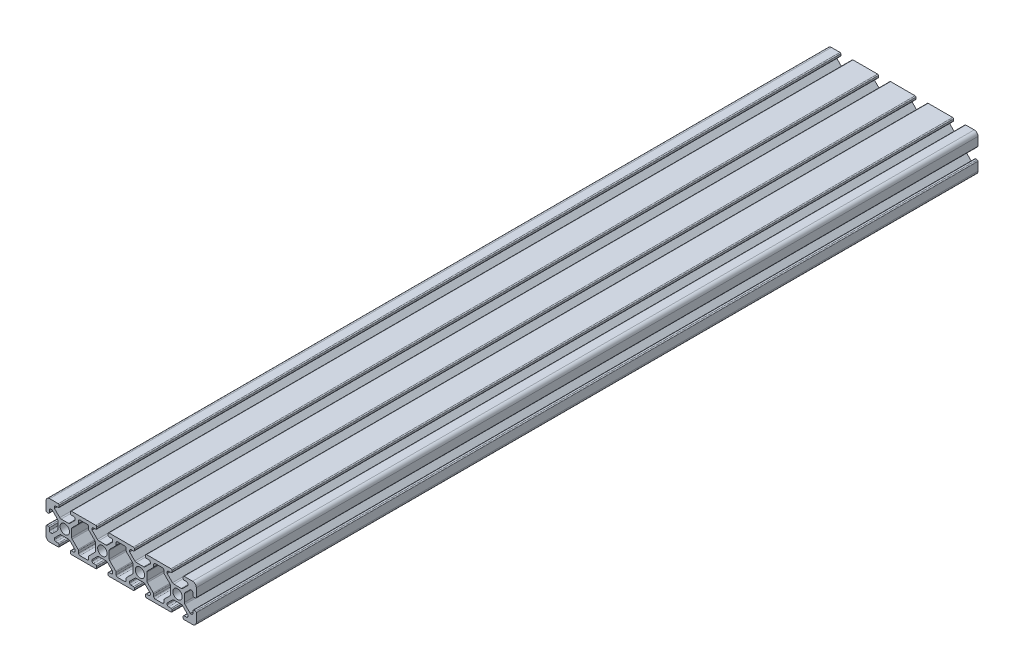
SolidWorks part; units mm, degrees
material "6063-T5"
ref_plane "Front Plane" through (0, 0, 0) normal (0, 0, 1) x (1, 0, 0)
ref_plane "Top Plane" through (0, 0, 0) normal (0, 1, 0) x (1, 0, 0)
ref_plane "Right Plane" through (0, 0, 0) normal (1, 0, 0) x (0, 0, -1)
sketch "Sketch1" plane through (0, 0, 0) normal (0, 0, 1) x (1, 0, 0)
  line L0 (-41.935, 2.3415) -> (-37.435, 2.3415)
  line L1 (36.065, 4.3415) -> (36.065, 8.8415)
  line L2 (34.065, 22.3415) -> (29.565, 22.3415)
  line L3 (-43.935, 20.3415) -> (-43.935, 15.8415)
  line L4 (-10.935, 21.8415) -> (-10.935, 21.0415)
  line L5 (-16.935, 21.8415) -> (-16.935, 21.0415)
  line L6 (-36.935, 21.8415) -> (-36.935, 21.0415)
  line L7 (-30.935, 21.8415) -> (-30.935, 21.0415)
  line L8 (-37.435, 22.3415) -> (-41.935, 22.3415)
  line L9 (9.065, 21.8415) -> (9.065, 21.0415)
  line L10 (3.065, 21.8415) -> (3.065, 21.0415)
  line L11 (29.065, 21.8415) -> (29.065, 21.0415)
  line L12 (23.065, 21.8415) -> (23.065, 21.0415)
  line L13 (-10.935, 3.6415) -> (-10.935, 2.8415)
  line L14 (-16.935, 3.6415) -> (-16.935, 2.8415)
  line L15 (9.065, 3.6415) -> (9.065, 2.8415)
  line L16 (3.065, 3.6415) -> (3.065, 2.8415)
  line L17 (29.065, 3.6415) -> (29.065, 2.8415)
  line L18 (23.065, 3.6415) -> (23.065, 2.8415)
  line L19 (-30.935, 3.6415) -> (-30.935, 2.8415)
  line L20 (-36.935, 3.6415) -> (-36.935, 2.8415)
  line L21 (-30.435, 22.3415) -> (-17.435, 22.3415) construction
  line L22 (-17.435, 22.3415) -> (-30.435, 22.3415)
  line L23 (2.565, 22.3415) -> (-10.435, 22.3415)
  line L24 (22.565, 22.3415) -> (9.565, 22.3415)
  line L25 (29.565, 2.3415) -> (34.065, 2.3415)
  line L26 (9.565, 2.3415) -> (22.565, 2.3415)
  line L27 (-10.435, 2.3415) -> (2.565, 2.3415)
  line L28 (-30.435, 2.3415) -> (-17.435, 2.3415)
  line L29 (35.565, 15.3415) -> (34.765, 15.3415)
  line L30 (35.565, 9.3415) -> (34.765, 9.3415)
  line L31 (-43.435, 15.3415) -> (-42.635, 15.3415)
  line L32 (-43.435, 9.3415) -> (-42.635, 9.3415)
  line L33 (-43.935, 8.8415) -> (-43.935, 4.3415)
  line L34 (36.065, 15.8415) -> (36.065, 20.3415)
  line L35 (-42.135, 15.8415) -> (-42.135, 17.0915)
  line L36 (-38.685, 20.5415) -> (-37.435, 20.5415)
  line L37 (34.265, 17.0915) -> (34.265, 15.8415)
  line L38 (30.815, 4.1415) -> (29.565, 4.1415)
  line L39 (-42.135, 7.5915) -> (-42.135, 8.8415)
  line L40 (-30.435, 20.5415) -> (-29.185, 20.5415)
  line L41 (-37.435, 4.1415) -> (-38.685, 4.1415)
  line L42 (-10.435, 20.5415) -> (-9.185, 20.5415)
  line L43 (-17.435, 4.1415) -> (-18.685, 4.1415)
  line L44 (9.565, 20.5415) -> (10.815, 20.5415)
  line L45 (2.565, 4.1415) -> (1.315, 4.1415)
  line L46 (29.565, 20.5415) -> (30.815, 20.5415)
  line L47 (22.565, 4.1415) -> (21.315, 4.1415)
  line L48 (34.265, 8.8415) -> (34.265, 7.5915)
  line L49 (-31.2649, 16.2843) -> (-28.435, 19.1142)
  line L50 (-31.2649, 8.3986) -> (-28.435, 5.5687)
  line L51 (-11.2649, 16.2843) -> (-8.435, 19.1142)
  line L52 (-9.9921, 15.0116) -> (-6.8546, 18.149)
  line L53 (-16.6051, 16.2843) -> (-19.435, 19.1142)
  line L54 (-21.0153, 18.149) -> (-17.8778, 15.0116)
  line L55 (-16.6051, 8.3986) -> (-19.435, 5.5687)
  line L56 (-21.0153, 6.5339) -> (-17.8778, 9.6714)
  line L57 (3.3949, 16.2843) -> (0.565, 19.1142)
  line L58 (-1.0153, 18.149) -> (2.1222, 15.0116)
  line L59 (3.3949, 8.3986) -> (0.565, 5.5687)
  line L60 (-1.0153, 6.5339) -> (2.1222, 9.6714)
  line L61 (23.3949, 16.2843) -> (20.565, 19.1142)
  line L62 (18.9847, 18.149) -> (22.1222, 15.0116)
  line L63 (23.3949, 8.3986) -> (20.565, 5.5687)
  line L64 (18.9847, 6.5339) -> (22.1222, 9.6714)
  line L65 (-9.9921, 9.6714) -> (-6.8546, 6.5339)
  line L66 (-29.9921, 15.0116) -> (-26.8546, 18.149)
  line L67 (-37.8778, 9.6714) -> (-40.7077, 6.8415)
  line L68 (-36.6051, 8.3986) -> (-39.435, 5.5687)
  line L69 (-36.6051, 16.2843) -> (-39.435, 19.1142)
  line L70 (-11.2649, 8.3986) -> (-8.435, 5.5687)
  line L71 (-29.9921, 9.6714) -> (-26.8546, 6.5339)
  line L72 (8.7351, 16.2843) -> (11.565, 19.1142)
  line L73 (-37.8778, 15.0116) -> (-40.7077, 17.8415)
  line L74 (10.0079, 15.0116) -> (13.1454, 18.149)
  line L75 (10.0079, 9.6714) -> (13.1454, 6.5339)
  line L76 (8.7351, 8.3986) -> (11.565, 5.5687)
  line L77 (28.7351, 16.2843) -> (31.565, 19.1142)
  line L78 (30.0079, 15.0116) -> (32.8378, 17.8415)
  line L79 (30.0079, 9.6714) -> (32.8378, 6.8415)
  line L80 (28.7351, 8.3986) -> (31.565, 5.5687)
  line L81 (-15.898, 15.9915) -> (-11.972, 15.9915)
  line L82 (-25.885, 20.5415) -> (-21.985, 20.5415)
  line L83 (-29.185, 4.1415) -> (-30.435, 4.1415)
  line L84 (-28.435, 19.7915) -> (-28.435, 19.1142)
  line L85 (-9.185, 4.1415) -> (-10.435, 4.1415)
  line L86 (-39.435, 19.7915) -> (-39.435, 19.1142)
  line L87 (10.815, 4.1415) -> (9.565, 4.1415)
  line L88 (-19.435, 19.7915) -> (-19.435, 19.1142)
  line L89 (-18.685, 20.5415) -> (-17.435, 20.5415)
  line L90 (1.315, 20.5415) -> (2.565, 20.5415)
  line L91 (-10.285, 14.3044) -> (-10.285, 10.3785)
  line L92 (-11.972, 8.6915) -> (-15.898, 8.6915)
  line L93 (-17.585, 10.3785) -> (-17.585, 14.3044)
  line L94 (21.315, 20.5415) -> (22.565, 20.5415)
  line L95 (0.565, 19.7915) -> (0.565, 19.1142)
  line L96 (-8.435, 19.7915) -> (-8.435, 19.1142)
  line L97 (-30.285, 14.3044) -> (-30.285, 10.3785)
  line L98 (-31.972, 8.6915) -> (-35.898, 8.6915)
  line L99 (-37.585, 10.3785) -> (-37.585, 14.3044)
  line L100 (-35.898, 15.9915) -> (-31.972, 15.9915)
  line L101 (4.102, 15.9915) -> (8.028, 15.9915)
  line L102 (9.715, 14.3044) -> (9.715, 10.3785)
  line L103 (8.028, 8.6915) -> (4.102, 8.6915)
  line L104 (2.415, 10.3785) -> (2.415, 14.3044)
  line L105 (24.102, 15.9915) -> (28.028, 15.9915)
  line L106 (29.715, 14.3044) -> (29.715, 10.3785)
  line L107 (28.028, 8.6915) -> (24.102, 8.6915)
  line L108 (22.415, 10.3785) -> (22.415, 14.3044)
  line L109 (20.565, 19.7915) -> (20.565, 19.1142)
  line L110 (11.565, 19.7915) -> (11.565, 19.1142)
  line L111 (-39.435, 4.8915) -> (-39.435, 5.5687)
  line L112 (31.565, 19.7915) -> (31.565, 19.1142)
  line L113 (-19.435, 4.8915) -> (-19.435, 5.5687)
  line L114 (-28.435, 4.8915) -> (-28.435, 5.5687)
  line L115 (0.565, 4.8915) -> (0.565, 5.5687)
  line L116 (-8.435, 4.8915) -> (-8.435, 5.5687)
  line L117 (20.565, 4.8915) -> (20.565, 5.5687)
  line L118 (11.565, 4.8915) -> (11.565, 5.5687)
  line L119 (-41.385, 17.8415) -> (-40.7077, 17.8415)
  line L120 (31.565, 4.8915) -> (31.565, 5.5687)
  line L121 (-41.385, 6.8415) -> (-40.7077, 6.8415)
  line L122 (33.515, 17.8415) -> (32.8378, 17.8415)
  line L123 (-26.635, 19.7915) -> (-26.635, 18.6793)
  line L124 (33.515, 6.8415) -> (32.8378, 6.8415)
  line L125 (-21.235, 19.7915) -> (-21.235, 18.6793)
  line L126 (-5.885, 20.5415) -> (-1.985, 20.5415)
  line L127 (-6.635, 19.7915) -> (-6.635, 18.6793)
  line L128 (-1.235, 19.7915) -> (-1.235, 18.6793)
  line L129 (14.115, 20.5415) -> (18.015, 20.5415)
  line L130 (13.365, 19.7915) -> (13.365, 18.6793)
  line L131 (18.765, 19.7915) -> (18.765, 18.6793)
  line L132 (-26.635, 6.0036) -> (-26.635, 4.8915)
  line L133 (-25.885, 4.1415) -> (-21.985, 4.1415)
  line L134 (-21.235, 4.8915) -> (-21.235, 6.0036)
  line L135 (-6.635, 6.0036) -> (-6.635, 4.8915)
  line L136 (-5.885, 4.1415) -> (-1.985, 4.1415)
  line L137 (-1.235, 4.8915) -> (-1.235, 6.0036)
  line L138 (13.365, 6.0036) -> (13.365, 4.8915)
  line L139 (14.115, 4.1415) -> (18.015, 4.1415)
  line L140 (18.765, 4.8915) -> (18.765, 6.0036)
  circle A0 centre (-33.935, 12.3415) radius 2.5
  circle A1 centre (-13.935, 12.3415) radius 2.5
  circle A2 centre (6.065, 12.3415) radius 2.5
  circle A3 centre (26.065, 12.3415) radius 2.5
  arc A4 (34.065, 2.3415) -> (36.065, 4.3415) centre (34.065, 4.3415) ccw
  arc A5 (36.065, 20.3415) -> (34.065, 22.3415) centre (34.065, 20.3415) ccw
  arc A6 (-41.935, 2.3415) -> (-43.935, 4.3415) centre (-41.935, 4.3415) cw
  arc A7 (-41.935, 22.3415) -> (-43.935, 20.3415) centre (-41.935, 20.3415) ccw
  arc A8 (-31.2649, 16.2843) -> (-31.972, 15.9915) centre (-31.972, 16.9915) cw
  arc A9 (-36.6051, 16.2843) -> (-35.898, 15.9915) centre (-35.898, 16.9915) ccw
  arc A10 (-37.8778, 15.0116) -> (-37.585, 14.3044) centre (-38.585, 14.3044) cw
  arc A11 (-37.8778, 9.6714) -> (-37.585, 10.3785) centre (-38.585, 10.3785) ccw
  arc A12 (-36.6051, 8.3986) -> (-35.898, 8.6915) centre (-35.898, 7.6915) cw
  arc A13 (-31.2649, 8.3986) -> (-31.972, 8.6915) centre (-31.972, 7.6915) ccw
  arc A14 (-11.2649, 8.3986) -> (-11.972, 8.6915) centre (-11.972, 7.6915) ccw
  arc A15 (-16.6051, 8.3986) -> (-15.898, 8.6915) centre (-15.898, 7.6915) cw
  arc A16 (-16.6051, 16.2843) -> (-15.898, 15.9915) centre (-15.898, 16.9915) ccw
  arc A17 (-11.2649, 16.2843) -> (-11.972, 15.9915) centre (-11.972, 16.9915) cw
  arc A18 (3.3949, 8.3986) -> (4.102, 8.6915) centre (4.102, 7.6915) cw
  arc A19 (8.7351, 8.3986) -> (8.028, 8.6915) centre (8.028, 7.6915) ccw
  arc A20 (8.7351, 16.2843) -> (8.028, 15.9915) centre (8.028, 16.9915) cw
  arc A21 (3.3949, 16.2843) -> (4.102, 15.9915) centre (4.102, 16.9915) ccw
  arc A22 (28.7351, 16.2843) -> (28.028, 15.9915) centre (28.028, 16.9915) cw
  arc A23 (23.3949, 16.2843) -> (24.102, 15.9915) centre (24.102, 16.9915) ccw
  arc A24 (23.3949, 8.3986) -> (24.102, 8.6915) centre (24.102, 7.6915) cw
  arc A25 (28.7351, 8.3986) -> (28.028, 8.6915) centre (28.028, 7.6915) ccw
  arc A26 (30.0079, 9.6714) -> (29.715, 10.3785) centre (30.715, 10.3785) cw
  arc A27 (30.0079, 15.0116) -> (29.715, 14.3044) centre (30.715, 14.3044) ccw
  arc A28 (22.1222, 9.6714) -> (22.415, 10.3785) centre (21.415, 10.3785) ccw
  arc A29 (22.1222, 15.0116) -> (22.415, 14.3044) centre (21.415, 14.3044) cw
  arc A30 (10.0079, 9.6714) -> (9.715, 10.3785) centre (10.715, 10.3785) cw
  arc A31 (10.0079, 15.0116) -> (9.715, 14.3044) centre (10.715, 14.3044) ccw
  arc A32 (34.265, 17.0915) -> (33.515, 17.8415) centre (33.515, 17.0915) ccw
  arc A33 (31.565, 19.7915) -> (30.815, 20.5415) centre (30.815, 19.7915) ccw
  arc A34 (34.265, 7.5915) -> (33.515, 6.8415) centre (33.515, 7.5915) cw
  arc A35 (31.565, 4.8915) -> (30.815, 4.1415) centre (30.815, 4.8915) cw
  arc A36 (2.1222, 9.6714) -> (2.415, 10.3785) centre (1.415, 10.3785) ccw
  arc A37 (2.1222, 15.0116) -> (2.415, 14.3044) centre (1.415, 14.3044) cw
  arc A38 (-9.9921, 9.6714) -> (-10.285, 10.3785) centre (-9.285, 10.3785) cw
  arc A39 (-9.9921, 15.0116) -> (-10.285, 14.3044) centre (-9.285, 14.3044) ccw
  arc A40 (-29.9921, 15.0116) -> (-30.285, 14.3044) centre (-29.285, 14.3044) ccw
  arc A41 (-29.9921, 9.6714) -> (-30.285, 10.3785) centre (-29.285, 10.3785) cw
  arc A42 (-17.8778, 9.6714) -> (-17.585, 10.3785) centre (-18.585, 10.3785) ccw
  arc A43 (-17.8778, 15.0116) -> (-17.585, 14.3044) centre (-18.585, 14.3044) cw
  arc A44 (21.315, 4.1415) -> (20.565, 4.8915) centre (21.315, 4.8915) cw
  arc A45 (18.015, 4.1415) -> (18.765, 4.8915) centre (18.015, 4.8915) ccw
  arc A46 (13.365, 4.8915) -> (14.115, 4.1415) centre (14.115, 4.8915) ccw
  arc A47 (10.815, 4.1415) -> (11.565, 4.8915) centre (10.815, 4.8915) ccw
  arc A48 (1.315, 4.1415) -> (0.565, 4.8915) centre (1.315, 4.8915) cw
  arc A49 (20.565, 19.7915) -> (21.315, 20.5415) centre (21.315, 19.7915) cw
  arc A50 (18.015, 20.5415) -> (18.765, 19.7915) centre (18.015, 19.7915) cw
  arc A51 (14.115, 20.5415) -> (13.365, 19.7915) centre (14.115, 19.7915) ccw
  arc A52 (9.065, 21.0415) -> (9.565, 20.5415) centre (9.565, 21.0415) ccw
  arc A53 (9.065, 21.8415) -> (9.565, 22.3415) centre (9.565, 21.8415) cw
  arc A54 (23.065, 21.0415) -> (22.565, 20.5415) centre (22.565, 21.0415) cw
  arc A55 (23.065, 21.8415) -> (22.565, 22.3415) centre (22.565, 21.8415) ccw
  arc A56 (29.065, 21.0415) -> (29.565, 20.5415) centre (29.565, 21.0415) ccw
  arc A57 (29.065, 21.8415) -> (29.565, 22.3415) centre (29.565, 21.8415) cw
  arc A58 (34.765, 15.3415) -> (34.265, 15.8415) centre (34.765, 15.8415) cw
  arc A59 (35.565, 15.3415) -> (36.065, 15.8415) centre (35.565, 15.8415) ccw
  arc A60 (34.765, 9.3415) -> (34.265, 8.8415) centre (34.765, 8.8415) ccw
  arc A61 (35.565, 9.3415) -> (36.065, 8.8415) centre (35.565, 8.8415) cw
  arc A62 (29.065, 2.8415) -> (29.565, 2.3415) centre (29.565, 2.8415) ccw
  arc A63 (29.065, 3.6415) -> (29.565, 4.1415) centre (29.565, 3.6415) cw
  arc A64 (23.065, 2.8415) -> (22.565, 2.3415) centre (22.565, 2.8415) cw
  arc A65 (23.065, 3.6415) -> (22.565, 4.1415) centre (22.565, 3.6415) ccw
  arc A66 (9.065, 2.8415) -> (9.565, 2.3415) centre (9.565, 2.8415) ccw
  arc A67 (9.065, 3.6415) -> (9.565, 4.1415) centre (9.565, 3.6415) cw
  arc A68 (3.065, 2.8415) -> (2.565, 2.3415) centre (2.565, 2.8415) cw
  arc A69 (3.065, 3.6415) -> (2.565, 4.1415) centre (2.565, 3.6415) ccw
  arc A70 (-10.935, 2.8415) -> (-10.435, 2.3415) centre (-10.435, 2.8415) ccw
  arc A71 (-10.935, 3.6415) -> (-10.435, 4.1415) centre (-10.435, 3.6415) cw
  arc A72 (-16.935, 2.8415) -> (-17.435, 2.3415) centre (-17.435, 2.8415) cw
  arc A73 (-16.935, 3.6415) -> (-17.435, 4.1415) centre (-17.435, 3.6415) ccw
  arc A74 (3.065, 21.0415) -> (2.565, 20.5415) centre (2.565, 21.0415) cw
  arc A75 (3.065, 21.8415) -> (2.565, 22.3415) centre (2.565, 21.8415) ccw
  arc A76 (-10.935, 21.0415) -> (-10.435, 20.5415) centre (-10.435, 21.0415) ccw
  arc A77 (-10.935, 21.8415) -> (-10.435, 22.3415) centre (-10.435, 21.8415) cw
  arc A78 (-16.935, 21.0415) -> (-17.435, 20.5415) centre (-17.435, 21.0415) cw
  arc A79 (-16.935, 21.8415) -> (-17.435, 22.3415) centre (-17.435, 21.8415) ccw
  arc A80 (-30.935, 21.0415) -> (-30.435, 20.5415) centre (-30.435, 21.0415) ccw
  arc A81 (-30.435, 22.3415) -> (-30.935, 21.8415) centre (-30.435, 21.8415) ccw
  arc A82 (-30.935, 2.8415) -> (-30.435, 2.3415) centre (-30.435, 2.8415) ccw
  arc A83 (-30.935, 3.6415) -> (-30.435, 4.1415) centre (-30.435, 3.6415) cw
  arc A84 (-36.935, 2.8415) -> (-37.435, 2.3415) centre (-37.435, 2.8415) cw
  arc A85 (-36.935, 3.6415) -> (-37.435, 4.1415) centre (-37.435, 3.6415) ccw
  arc A86 (-43.935, 8.8415) -> (-43.435, 9.3415) centre (-43.435, 8.8415) cw
  arc A87 (-42.635, 9.3415) -> (-42.135, 8.8415) centre (-42.635, 8.8415) cw
  arc A88 (-43.935, 15.8415) -> (-43.435, 15.3415) centre (-43.435, 15.8415) ccw
  arc A89 (-42.635, 15.3415) -> (-42.135, 15.8415) centre (-42.635, 15.8415) ccw
  arc A90 (-37.435, 22.3415) -> (-36.935, 21.8415) centre (-37.435, 21.8415) cw
  arc A91 (-36.935, 21.0415) -> (-37.435, 20.5415) centre (-37.435, 21.0415) cw
  arc A92 (11.565, 19.7915) -> (10.815, 20.5415) centre (10.815, 19.7915) ccw
  arc A93 (0.565, 19.7915) -> (1.315, 20.5415) centre (1.315, 19.7915) cw
  arc A94 (-6.635, 4.8915) -> (-5.885, 4.1415) centre (-5.885, 4.8915) ccw
  arc A95 (-5.885, 20.5415) -> (-6.635, 19.7915) centre (-5.885, 19.7915) ccw
  arc A96 (-1.985, 20.5415) -> (-1.235, 19.7915) centre (-1.985, 19.7915) cw
  arc A97 (-1.985, 4.1415) -> (-1.235, 4.8915) centre (-1.985, 4.8915) ccw
  arc A98 (-9.185, 4.1415) -> (-8.435, 4.8915) centre (-9.185, 4.8915) ccw
  arc A99 (-18.685, 4.1415) -> (-19.435, 4.8915) centre (-18.685, 4.8915) cw
  arc A100 (-29.185, 4.1415) -> (-28.435, 4.8915) centre (-29.185, 4.8915) ccw
  arc A101 (-38.685, 4.1415) -> (-39.435, 4.8915) centre (-38.685, 4.8915) cw
  arc A102 (-41.385, 6.8415) -> (-42.135, 7.5915) centre (-41.385, 7.5915) cw
  arc A103 (-42.135, 17.0915) -> (-41.385, 17.8415) centre (-41.385, 17.0915) cw
  arc A104 (-19.435, 19.7915) -> (-18.685, 20.5415) centre (-18.685, 19.7915) cw
  arc A105 (-9.185, 20.5415) -> (-8.435, 19.7915) centre (-9.185, 19.7915) cw
  arc A106 (-21.985, 20.5415) -> (-21.235, 19.7915) centre (-21.985, 19.7915) cw
  arc A107 (-25.885, 20.5415) -> (-26.635, 19.7915) centre (-25.885, 19.7915) ccw
  arc A108 (-28.435, 19.7915) -> (-29.185, 20.5415) centre (-29.185, 19.7915) ccw
  arc A109 (-38.685, 20.5415) -> (-39.435, 19.7915) centre (-38.685, 19.7915) ccw
  arc A110 (18.765, 6.0036) -> (18.9847, 6.5339) centre (19.515, 6.0036) cw
  arc A111 (13.365, 6.0036) -> (13.1454, 6.5339) centre (12.615, 6.0036) ccw
  arc A112 (18.765, 18.6793) -> (18.9847, 18.149) centre (19.515, 18.6793) ccw
  arc A113 (13.365, 18.6793) -> (13.1454, 18.149) centre (12.615, 18.6793) cw
  arc A114 (-1.235, 6.0036) -> (-1.0153, 6.5339) centre (-0.485, 6.0036) cw
  arc A115 (-6.635, 6.0036) -> (-6.8546, 6.5339) centre (-7.385, 6.0036) ccw
  arc A116 (-1.235, 18.6793) -> (-1.0153, 18.149) centre (-0.485, 18.6793) ccw
  arc A117 (-6.635, 18.6793) -> (-6.8546, 18.149) centre (-7.385, 18.6793) cw
  arc A118 (-21.235, 18.6793) -> (-21.0153, 18.149) centre (-20.485, 18.6793) ccw
  arc A119 (-26.635, 18.6793) -> (-26.8546, 18.149) centre (-27.385, 18.6793) cw
  arc A120 (-26.635, 6.0036) -> (-26.8546, 6.5339) centre (-27.385, 6.0036) ccw
  arc A121 (-21.235, 6.0036) -> (-21.0153, 6.5339) centre (-20.485, 6.0036) cw
  arc A122 (-21.985, 4.1415) -> (-21.235, 4.8915) centre (-21.985, 4.8915) ccw
  arc A123 (-26.635, 4.8915) -> (-25.885, 4.1415) centre (-25.885, 4.8915) ccw
extrude "Boss-Extrude1" add sketch "Sketch1" along normal blind 416
